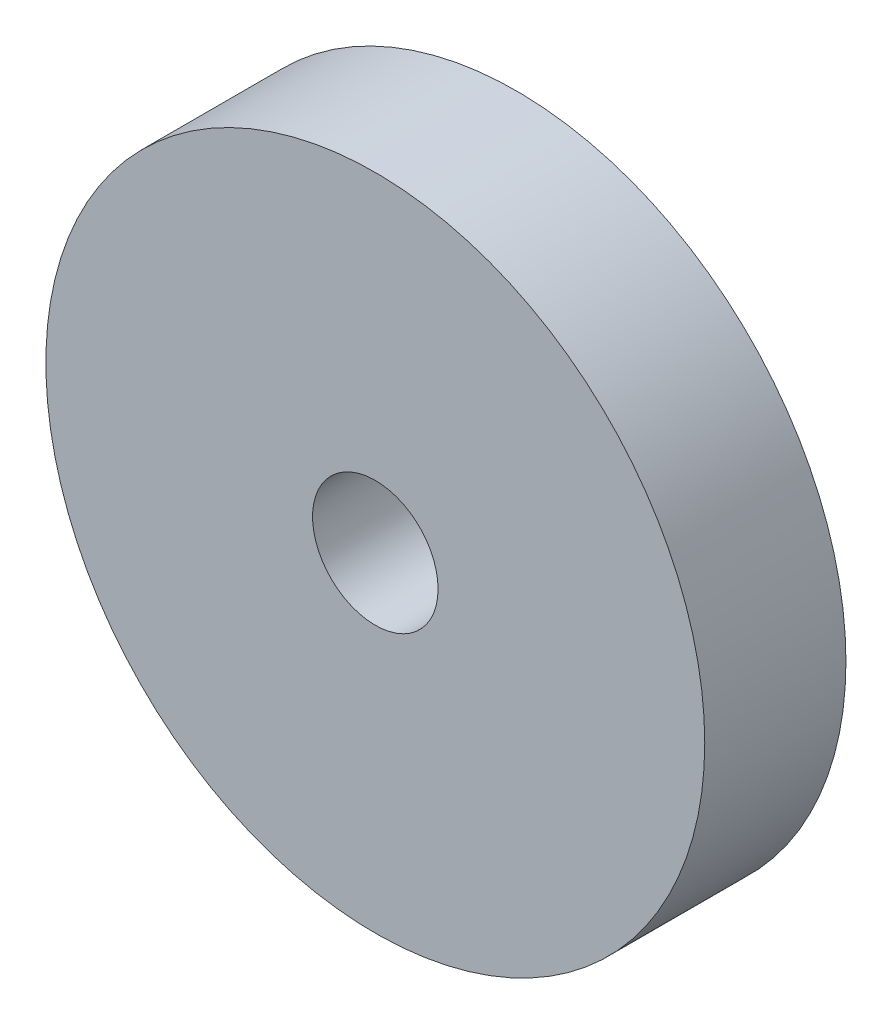
SolidWorks part; units mm, degrees
ref_plane "前视基准面" through (0, 0, 0) normal (0, 0, 1) x (1, 0, 0)
ref_plane "上视基准面" through (0, 0, 0) normal (0, 1, 0) x (1, 0, 0)
ref_plane "右视基准面" through (0, 0, 0) normal (1, 0, 0) x (0, 0, -1)
other "Configuration Table"
sketch "草图1" plane through (0, 0, 0) normal (0, 0, 1) x (1, 0, 0)
  circle A0 centre (0, 0) radius 42
  circle A1 centre (0, 0) radius 8
extrude "凸台-拉伸1" add sketch "草图1" along normal blind 18
sketch "草图2" plane through (0, 0, 0) normal (0, 0, 1) x (1, 0, 0)
  line L0 (37.5326, 2.0353) -> (37.6055, 2.0362)
  line L1 (37.6055, 2.0362) -> (37.8243, 2.0269)
  line L2 (37.8243, 2.0269) -> (38.1872, 1.9891)
  line L3 (38.1872, 1.9891) -> (38.6911, 1.905)
  line L4 (38.6911, 1.905) -> (39.3309, 1.7569)
  line L5 (39.3309, 1.7569) -> (40.1003, 1.5277)
  line L6 (40.1003, 1.5277) -> (40.9909, 1.2009)
  line L7 (40.9909, 1.2009) -> (41.9931, 0.7606)
  line L8 (41.9931, 0.7606) -> (41.9983, 0.3803)
  line L9 (41.9983, 0.3803) -> (42, 0)
  line L10 (42, 0) -> (41.9983, -0.3803)
  line L11 (41.9983, -0.3803) -> (41.9931, -0.7606)
  line L12 (41.9931, -0.7606) -> (40.9909, -1.2009)
  line L13 (40.9909, -1.2009) -> (40.1003, -1.5277)
  line L14 (40.1003, -1.5277) -> (39.3309, -1.7569)
  line L15 (39.3309, -1.7569) -> (38.6911, -1.905)
  line L16 (38.6911, -1.905) -> (38.1872, -1.9891)
  line L17 (38.1872, -1.9891) -> (37.5326, -2.0353)
  line L18 (37.5326, -2.0353) -> (37.6055, -2.0362)
  line L19 (37.6055, -2.0362) -> (37.5326, -2.0353)
  arc A0 (37.5326, -2.0353) -> (37.5326, 2.0353) centre (0, 0) ccw
